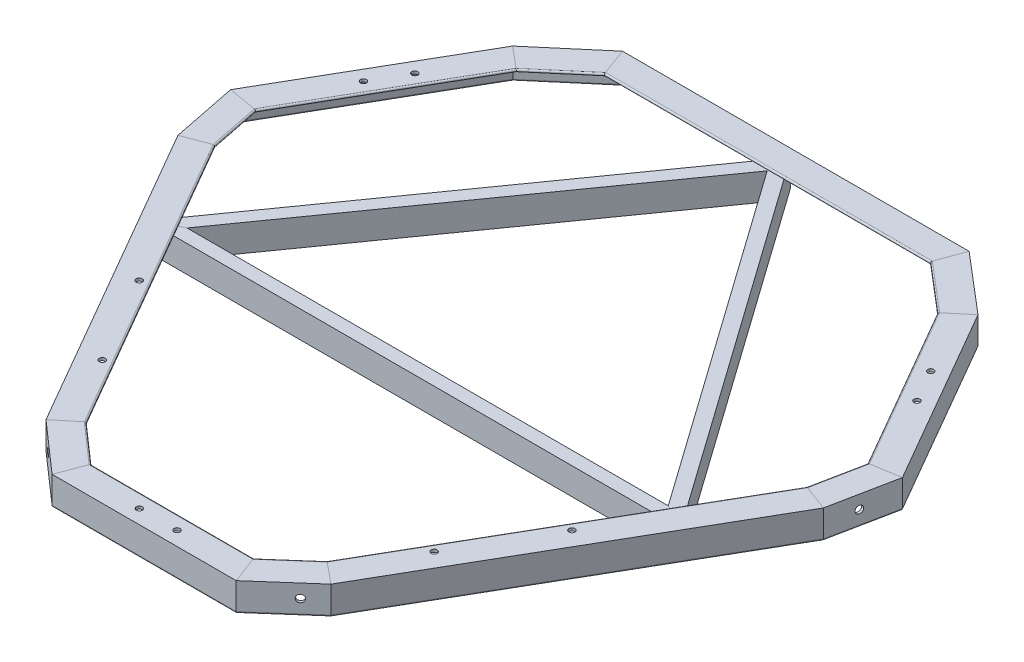
SolidWorks part; units mm, degrees
material "锻制不锈钢"
ref_plane "前视基准面" through (0, 0, 0) normal (0, 0, 1) x (1, 0, 0)
ref_plane "上视基准面" through (0, 0, 0) normal (0, 1, 0) x (1, 0, 0)
ref_plane "右视基准面" through (0, 0, 0) normal (1, 0, 0) x (0, 0, -1)
ref_plane "基准面1" through (0, 225, 0) normal (0, 1, 0) x (1, 0, 0)
sketch "草图2" plane through (0, 225, 0) normal (0, 1, 0) x (1, 0, 0)
  line L0 (0, 0) -> (0, 232.8132) construction
  line L1 (0, 0) -> (-213.2068, 123.095) construction
  line L2 (-173.1806, 192.4224) -> (-250, 59.3672)
  line L3 (-250, 59.3672) -> (-68.5, -255) construction
  line L4 (250, 59.3672) -> (68.5, -255) construction
  line L5 (173.1806, 192.4224) -> (250, 59.3672)
  line L6 (-129, 230) -> (129, 230)
  line L7 (-250, 59.3672) -> (-240.171, 10.3428)
  line L8 (-250, -255) -> (250, -255) construction
  line L9 (-250, -255) -> (-250, 245) construction
  line L10 (-250, 245) -> (250, 245) construction
  line L11 (250, -255) -> (250, 245) construction
  line L12 (-250, -255) -> (250, 245) construction
  line L13 (-250, 245) -> (250, -255) construction
  line L14 (-240.171, 10.3428) -> (-106.0418, -221.9756)
  line L15 (-68.5, -255) -> (-106.0418, -221.9756)
  line L17 (68.5, -255) -> (106.0418, -221.9756)
  line L19 (240.171, 10.3428) -> (106.0418, -221.9756)
  line L22 (250, 59.3672) -> (240.171, 10.3428)
  line L23 (-173.1806, 192.4224) -> (-129, 230)
  line L24 (173.1806, 192.4224) -> (129, 230)
  line L25 (0, 0) -> (0, 169.1465) construction
  line L26 (-144.4826, 115.7487) -> (-128.7326, 143.0285) construction
  line L27 (-188.2326, 39.9715) -> (-242.9568, 71.5665) construction
  line L28 (-188.2326, 39.9715) -> (-172.4826, 67.2513) construction
  line L29 (-242.9568, 71.5665) -> (-183.4568, 174.6235) construction
  line L30 (-128.7326, 143.0285) -> (-183.4568, 174.6235) construction
  line L31 (-188.2326, 39.9715) -> (-183.4568, 174.6235) construction
  line L32 (-242.9568, 71.5665) -> (-128.7326, 143.0285) construction
  line L33 (-124.8513, 39.7513) -> (-172.4826, 67.2513) construction
  line L34 (-124.8513, 39.7513) -> (-96.8513, 88.2487) construction
  line L35 (-178.0961, 171.5285) -> (-237.5961, 68.4715) construction
  line L36 (-96.8513, 88.2487) -> (-144.4826, 115.7487) construction
  line L37 (-124.8513, 39.7513) -> (-144.4826, 115.7487) construction
  line L38 (-172.4826, 67.2513) -> (-96.8513, 88.2487) construction
  line L39 (-68.5, -255) -> (68.5, -255)
  circle A0 centre (0, 0) radius 55
  point P9 (-185.8447, 107.2975)
  point P10 (-134.667, 77.75)
  point P19 (0, 0)
  point P22 (0, 0)
  point P27 (0, -5)
  point P43 (0, 0)
  dimension "D4" = 110
  dimension "D1" = 230
  dimension "D2" = 500
  dimension "D3" = 16
  dimension "D6" = 258
  dimension "D7" = 119
  dimension "D8" = 63.19
  dimension "D9" = 55
  dimension "D10" = 56
  dimension "D11" = 60
  dimension "D5" = 5
  dimension "D12" = 60
  dimension "D13" = 128
  dimension "D14" = 57
  dimension "D15" = 137
  dimension "D16" = 255
  dimension "D17" = 246.19
  dimension "D18" = 50
  dimension "D19" = 58
other "结构构件1"
ref_plane "基准面2" through (-129, 215, -220) normal (1, 0, 0) x (0, 0, 1)
sketch "Sketch1" plane through (-129, 215, -220) normal (1, 0, 0) x (0, 0, 1)
  line L0 (-8, 8) -> (0, 8) construction
  line L1 (-10, -10) -> (0, -10)
  line L2 (-10, -10) -> (-10, 5)
  line L3 (-10, 10) -> (0, 10) construction
  line L4 (10, -10) -> (10, 5) construction
  line L5 (-10, -10) -> (10, 10) construction
  line L6 (-10, 10) -> (10, -10) construction
  line L7 (8, -8) -> (8, 5) construction
  line L8 (-6, -8) -> (0, -8)
  line L9 (-8, -6) -> (-8, 5)
  line L10 (0, 6.1921) -> (0, -6.0984) construction
  line L11 (-10.856, 0) -> (10.9594, 0) construction
  line L12 (0, 10) -> (10, 10) construction
  line L13 (-10, 10) -> (10, 10) construction
  line L14 (0, 8) -> (8, 8) construction
  line L15 (-8, 8) -> (8, 8) construction
  line L16 (8, 5) -> (8, 8) construction
  line L17 (8, -8) -> (8, 8) construction
  line L18 (10, 5) -> (10, 10) construction
  line L19 (10, -10) -> (10, 10) construction
  line L20 (-8, 5) -> (-8, 10)
  line L21 (-8, -8) -> (-8, 8) construction
  line L22 (-10, 5) -> (-10, 10)
  line L23 (-10, -10) -> (-10, 10) construction
  line L24 (0, -10) -> (10, -10)
  line L25 (-10, -10) -> (10, -10) construction
  line L26 (0, -8) -> (10, -8)
  line L27 (-8, -8) -> (8, -8) construction
  arc A0 (-8, -6) -> (-6, -8) centre (-6, -6) ccw
  arc A1 (-8, 10) -> (-10, 10) centre (-9, 10) ccw
  arc A2 (10, -10) -> (10, -8) centre (10, -9) ccw
  point P0 (0, 0)
  point P28 (0, 0)
  dimension "D1" = 20
  dimension "D2" = 20
  dimension "D3" = 2
  dimension "D4" = 2
mirror "镜向1" [suppressed] about plane through (0, 0, 0) normal (1, 0, 0)
ref_plane "基准面5" through (0, 104, 0) normal (0, 1, 0) x (1, 0, 0)
sketch "草图14" plane through (0, 223, 0) normal (0, -1, 0) x (1, 0, 0)
  line L0 (0, 0) -> (0, -332.032) construction
  line L1 (0, -226) -> (198.4038, 54)
  line L4 (0, -226) -> (-198.4038, 54)
  line L5 (-198.4038, 54) -> (198.4038, 54)
  line L6 (127.529, -226) -> (-127.529, -226) construction
  line L7 (-236.3782, -11.7736) -> (-102.9064, 219.4064) construction
  dimension "D1" = 280
other "结构构件3"
ref_plane "基准面6" through (4.0796, 213, -223.1092) normal (-0.5782, 0, 0.8159) x (0, -1, 0)
sketch "Sketch13" plane through (4.0796, 213, -223.1092) normal (-0.5782, 0, 0.8159) x (0, -1, 0)
  line L0 (-9, 4) -> (0, 4)
  line L1 (-10, -5) -> (0, -5)
  line L2 (-10, -5) -> (-10, 0)
  line L3 (-10, 5) -> (0, 5)
  line L4 (10, -5) -> (10, 0)
  line L5 (-10, -5) -> (10, 5) construction
  line L6 (-10, 5) -> (10, -5) construction
  line L7 (9, -4) -> (9, 0)
  line L8 (-9, -4) -> (0, -4)
  line L9 (-9, -4) -> (-9, 0)
  line L10 (0, 6.1921) -> (0, -6.0984) construction
  line L11 (-10.856, 0) -> (10.9594, 0) construction
  line L12 (0, 5) -> (10, 5)
  line L13 (-10, 5) -> (10, 5) construction
  line L14 (0, 4) -> (9, 4)
  line L15 (-9, 4) -> (9, 4) construction
  line L16 (9, 0) -> (9, 4)
  line L17 (9, -4) -> (9, 4) construction
  line L18 (10, 0) -> (10, 5)
  line L19 (10, -5) -> (10, 5) construction
  line L20 (-9, 0) -> (-9, 4)
  line L21 (-9, -4) -> (-9, 4) construction
  line L22 (-10, 0) -> (-10, 5)
  line L23 (-10, -5) -> (-10, 5) construction
  line L24 (0, -5) -> (10, -5)
  line L25 (-10, -5) -> (10, -5) construction
  line L26 (0, -4) -> (9, -4)
  line L27 (-9, -4) -> (9, -4) construction
  point P0 (0, 0)
  point P13 (0, 0)
  dimension "D1" = 20
  dimension "D2" = 10
  dimension "D3" = 1
hole_wizard "M5 间隙孔1" positions "草图18" profile "草图17" hole size "M5" standard "GB" end condition up to next
sketch "草图18" plane through (-167.6588, 0, -197.1189) normal (-0.6479, 0, -0.7617) x (-0.7617, 0, 0.6479)
  point P0 (-19.0061, 215)
sketch "草图17" plane through (-153.1812, 215, -209.4328) normal (0, 1, 0) x (-0.7617, 0, 0.6479)
  line L0 (0, 0) -> (0, 334.0179)
  line L1 (0, 334.0179) -> (2.75, 334.0179)
  line L2 (2.75, 334.0179) -> (2.75, 0)
  line L5 (2.75, 0) -> (0, 0)
  line L11 (0, -6.35) -> (0, 107.95) construction
  dimension "通孔孔直径" = 5.5
  dimension "通孔孔深度" = 334.0179
hole_wizard "M5 间隙孔2" positions "草图20" profile "草图19" hole size "M5" standard "GB" end condition up to next
sketch "草图20" plane through (-228.8963, 0, 45.892) normal (-0.9805, 0, 0.1966) x (0.1966, 0, 0.9805)
  point P0 (-80.1043, 215)
sketch "草图19" plane through (-244.6432, 215, -32.6492) normal (0, 1, 0) x (0.1966, 0, 0.9805)
  line L0 (0, 0) -> (0, 11.4297)
  line L1 (0, 11.4297) -> (2.75, 11.4297)
  line L2 (2.75, 11.4297) -> (2.75, 0)
  line L5 (2.75, 0) -> (0, 0)
  line L11 (0, -6.35) -> (0, 107.95) construction
  dimension "通孔孔直径" = 5.5
  dimension "通孔孔深度" = 11.4297
hole_wizard "M5 间隙孔3" positions "草图22" profile "草图21" hole size "M5" standard "GB" end condition up to next
sketch "草图22" plane through (-156.3419, 0, 177.7282) normal (-0.6605, 0, 0.7508) x (0.7508, 0, 0.6605)
  point P0 (83.1341, 215)
sketch "草图21" plane through (-93.9218, 215, 232.6373) normal (0, 1, 0) x (0.7508, 0, 0.6605)
  line L0 (0, 0) -> (0, 239.2494)
  line L1 (0, 239.2494) -> (2.75, 239.2494)
  line L2 (2.75, 239.2494) -> (2.75, 0)
  line L5 (2.75, 0) -> (0, 0)
  line L11 (0, -6.35) -> (0, 107.95) construction
  dimension "通孔孔直径" = 5.5
  dimension "通孔孔深度" = 239.2494
sketch "草图23" plane through (0, 225, 0) normal (0, 1, 0) x (1, 0, 0)
  line L0 (0, -128.6238) -> (0, -182.3915) construction
  line L1 (-169.688, -92.6238) -> (-126.3868, -167.6238)
  line L2 (-126.3868, -167.6238) -> (126.3868, -167.6238)
  line L3 (169.688, -92.6238) -> (126.3868, -167.6238)
  line L4 (-169.688, -92.6238) -> (169.688, -92.6238)
  line L6 (-161.0278, -97.6238) -> (161.0278, -97.6238) construction
  line L7 (-161.0278, -97.6238) -> (-123.5, -162.6238) construction
  line L8 (-123.5, -162.6238) -> (123.5, -162.6238) construction
  line L9 (161.0278, -97.6238) -> (123.5, -162.6238) construction
  line L10 (-161.0278, -97.6238) -> (123.5, -162.6238) construction
  line L11 (-123.5, -162.6238) -> (161.0278, -97.6238) construction
  line L12 (-122.5, -144.6238) -> (122.5, -144.6238) construction
  line L13 (-122.5, -144.6238) -> (-122.5, -112.6238) construction
  line L14 (-122.5, -112.6238) -> (122.5, -112.6238) construction
  line L15 (122.5, -144.6238) -> (122.5, -112.6238) construction
  line L16 (-122.5, -144.6238) -> (122.5, -112.6238) construction
  line L17 (-122.5, -112.6238) -> (122.5, -144.6238) construction
  point P6 (0, -134.4103)
  dimension "D2" = 5
  dimension "D1" = 15
  dimension "D4" = 247
  dimension "D6" = 32
  dimension "D7" = 245
  dimension "D8" = 18
  dimension "D9" = 120
hole_wizard "M4 间隙孔1" positions "草图25" profile "草图24" hole size "M4" standard "GB" end condition up to next
sketch "草图25" plane through (0, 225, 0) normal (0, 1, 0) x (1, 0, 0)
  point P0 (-161.0278, -97.6238)
  point P3 (-123.5, -162.6238)
  point P6 (123.5, -162.6238)
  point P9 (161.0278, -97.6238)
sketch "草图24" plane through (-161.0278, 225, 97.6238) normal (1, 0, 0) x (0, 0, 1)
  line L0 (0, 0) -> (0, 2.001)
  line L1 (0, 2.001) -> (2.25, 2.001)
  line L2 (2.25, 2.001) -> (2.25, 0)
  line L5 (2.25, 0) -> (0, 0)
  line L11 (0, -6.35) -> (0, 107.95) construction
  dimension "通孔孔直径" = 4.5
  dimension "通孔孔深度" = 2.001
hole_wizard "M4 间隙孔2" positions "草图27" profile "草图26" hole size "M4" standard "GB" end condition up to next
sketch "草图27" plane through (0, 225, 0) normal (0, 1, 0) x (1, 0, 0)
  point P0 (-14, -244.5)
  point P3 (-205.9875, 114.2193)
  point P6 (-191.9875, 138.468)
sketch "草图26" plane through (-14, 225, 244.5) normal (1, 0, 0) x (0, 0, 1)
  line L0 (0, 0) -> (0, 2.001)
  line L1 (0, 2.001) -> (2.25, 2.001)
  line L2 (2.25, 2.001) -> (2.25, 0)
  line L5 (2.25, 0) -> (0, 0)
  line L11 (0, -6.35) -> (0, 107.95) construction
  dimension "通孔孔直径" = 4.5
  dimension "通孔孔深度" = 2.001
mirror "镜向2" about plane through (0, 0, 0) normal (1, 0, 0) of "M4 间隙孔2", "M5 间隙孔1", "M5 间隙孔2", "M5 间隙孔3"
